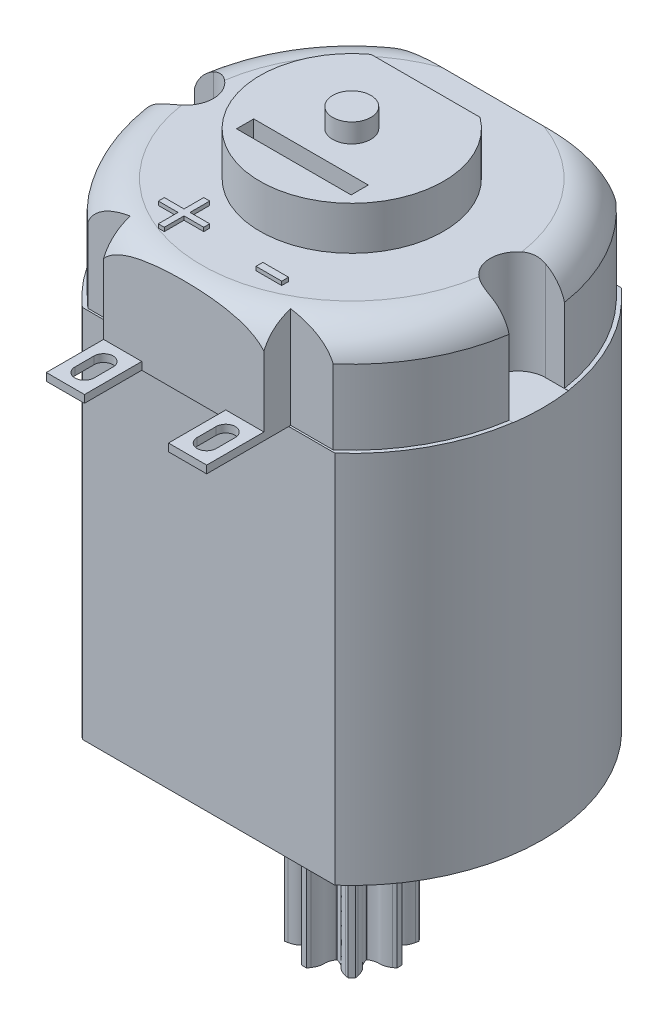
SolidWorks part; units mm, degrees
material "6061-T6 "
ref_plane "Front Plane" through (0, 0, 0) normal (0, 0, 1) x (1, 0, 0)
ref_plane "Top Plane" through (0, 0, 0) normal (0, 1, 0) x (1, 0, 0)
ref_plane "Right Plane" through (0, 0, 0) normal (1, 0, 0) x (0, 0, -1)
sketch "Sketch1" plane through (0, 0, 0) normal (0, 1, 0) x (1, 0, 0)
  line L0 (0, 22.8745) -> (0, 0) construction
  line L1 (0, 0) -> (42.3314, 0) construction
  line L2 (-6.6144, 7.5) -> (6.6144, 7.5)
  line L3 (-6.6144, -7.5) -> (6.6144, -7.5)
  arc A0 (6.6144, -7.5) -> (6.6144, 7.5) centre (0, 0) ccw
  arc A1 (-6.6144, -7.5) -> (-6.6144, 7.5) centre (0, 0) cw
  point P9 (0, 7.5)
  dimension "D1" = 15
  dimension "D2" = 10
extrude "Boss-Extrude1" add sketch "Sketch1" along normal mid plane 19.6
sketch "Sketch2" plane through (0, 9.8, 0) normal (0, 1, 0) x (1, 0, 0)
  line L0 (0, 10.5973) -> (0, 0) construction
  line L1 (0, 0) -> (15.8034, 0) construction
  line L2 (-6.425, 7.4) -> (6.425, 7.4)
  line L3 (-6.425, -7.4) -> (6.425, -7.4)
  arc A0 (6.425, 7.4) -> (6.425, -7.4) centre (0, 0) cw
  arc A1 (-6.425, 7.4) -> (-6.425, -7.4) centre (0, 0) ccw
  point P9 (0, -7.4)
  point P10 (0, 7.4)
  dimension "D1" = 9.8
  dimension "D2" = 14.8
extrude "Boss-Extrude2" add sketch "Sketch2" along normal offset from surface (5.4 mm away) 25 up to face at (0, -9.8, 0)
sketch "Sketch3" plane through (0, 0, 7.4) normal (0, 0, 1) x (1, 0, 0)
  line L0 (-6.425, 9.8) -> (6.425, 9.8) construction
  line L1 (-4.2, 15.2) -> (4.2, 15.2)
  line L2 (-4.2, 15.2) -> (-4.2, 9.8)
  line L3 (-4.2, 9.8) -> (4.2, 9.8)
  line L4 (4.2, 15.2) -> (4.2, 9.8)
  line L5 (-4.2, 15.2) -> (4.2, 9.8) construction
  line L6 (-4.2, 9.8) -> (4.2, 15.2) construction
  line L7 (0, 12.5) -> (0, 0) construction
  line L8 (-6.425, 15.2) -> (6.425, 15.2) construction
  point P0 (0, 12.5)
  dimension "D1" = 8.4
extrude "Boss-Extrude3" add sketch "Sketch3" along normal blind 1.4
sketch "Sketch4" plane through (0, 0, 0) normal (0, 0, 1) x (1, 0, 0)
  line L0 (0, 0) -> (0, 15.2695) construction
  line L1 (7.8635, 15.2) -> (9.8, 15.2)
  line L2 (9.8, 15.2) -> (9.8, 13.7)
  line L3 (9.8, 9.8) -> (9.8, 15.2) construction
  arc A0 (9.8, 13.7) -> (7.8635, 15.2) centre (7.8635, 13.2) ccw
  dimension "D1" = 2
  dimension "D2" = 1.5
revolve "Cut-Revolve1" cut sketch "Sketch4" angle 360 about L0
sketch "Sketch5" plane through (0, 15.2, 0) normal (0, 1, 0) x (1, 0, 0)
  line L0 (-2.8548, 3.865) -> (2.8548, 3.865)
  line L1 (0, -4.805) -> (13.2763, -4.805) construction
  arc A0 (-2.8548, 3.865) -> (2.8548, 3.865) centre (0, 0) ccw
  dimension "D1" = 9.61
  dimension "D3" = 8.67
extrude "Boss-Extrude4" add sketch "Sketch5" along normal blind 2.27
sketch "Sketch6" plane through (0, 17.47, 0) normal (0, 1, 0) x (1, 0, 0)
  line L0 (2.8548, 3.865) -> (-2.8548, 3.865) construction
  line L1 (-3, -2.135) -> (3, -2.135)
  line L2 (-3, -2.135) -> (-3, -3.035)
  line L3 (-3, -3.035) -> (3, -3.035)
  line L4 (3, -2.135) -> (3, -3.035)
  line L5 (-3, -2.135) -> (3, -3.035) construction
  line L6 (-3, -3.035) -> (3, -2.135) construction
  line L7 (0, -2.585) -> (0, 0) construction
  point P0 (0, -2.585)
  dimension "D1" = 6
  dimension "D2" = 0.9
  dimension "D3" = 6
extrude "Cut-Extrude1" cut sketch "Sketch6" against normal up to surface (2.27 mm away) up to face at (0, 15.2, 0.2318)
sketch "Sketch7" plane through (0, -9.8, 0) normal (0, -1, 0) x (1, 0, 0)
  circle A0 centre (0, 0) radius 3
  dimension "D1" = 6
extrude "Boss-Extrude5" add sketch "Sketch7" along normal blind 1.7
sketch "Sketch8" plane through (0, -11.5, 0) normal (0, -1, 0) x (1, 0, 0)
  circle A0 centre (0, 0) radius 1
  dimension "D1" = 2
extrude "Boss-Extrude6" add sketch "Sketch8" along normal offset from surface (7.8 mm away) 9.5 up to face at (0, -9.8, 0) offset beyond the face yes
sketch "Sketch9" plane through (0, -19.3, 0) normal (0, -1, 0) x (1, 0, 0)
  line L0 (0, 0) -> (-1.7678, 1.7678) construction
  line L1 (0, 0) -> (-0.5511, 1.3305) construction
  line L2 (0, 0) -> (-1.3305, 0.5511) construction
  arc A0 (-1.6695, 1.8608) -> (-1.8608, 1.6695) centre (0, 0) ccw
  arc A1 (-0.5874, 1.3368) -> (-0.5511, 1.3305) centre (-0.5363, 1.5249) ccw
  arc A2 (-1.3368, 0.5874) -> (-1.3305, 0.5511) centre (-1.5249, 0.5363) cw
  arc A3 (0.5299, 1.3606) -> (0.5511, 1.3305) centre (0.6991, 1.4575) ccw
  arc A4 (0.1352, 2.4963) -> (-0.1352, 2.4963) centre (0, 0) ccw
  arc A5 (-0.5299, 1.3606) -> (-0.5511, 1.3305) centre (-0.6991, 1.4575) cw
  arc A6 (1.3368, 0.5874) -> (1.3305, 0.5511) centre (1.5249, 0.5363) ccw
  arc A7 (1.8608, 1.6695) -> (1.6695, 1.8608) centre (0, 0) ccw
  arc A8 (0.5874, 1.3368) -> (0.5511, 1.3305) centre (0.5363, 1.5249) cw
  arc A9 (1.3606, -0.5299) -> (1.3305, -0.5511) centre (1.4575, -0.6991) ccw
  arc A10 (2.4963, -0.1352) -> (2.4963, 0.1352) centre (0, 0) ccw
  arc A11 (1.3606, 0.5299) -> (1.3305, 0.5511) centre (1.4575, 0.6991) cw
  arc A12 (0.5874, -1.3368) -> (0.5511, -1.3305) centre (0.5363, -1.5249) ccw
  arc A13 (1.6695, -1.8608) -> (1.8608, -1.6695) centre (0, 0) ccw
  arc A14 (1.3368, -0.5874) -> (1.3305, -0.5511) centre (1.5249, -0.5363) cw
  arc A15 (-0.5299, -1.3606) -> (-0.5511, -1.3305) centre (-0.6991, -1.4575) ccw
  arc A16 (-0.1352, -2.4963) -> (0.1352, -2.4963) centre (0, 0) ccw
  arc A17 (0.5299, -1.3606) -> (0.5511, -1.3305) centre (0.6991, -1.4575) cw
  arc A18 (-1.3368, -0.5874) -> (-1.3305, -0.5511) centre (-1.5249, -0.5363) ccw
  arc A19 (-1.8608, -1.6695) -> (-1.6695, -1.8608) centre (0, 0) ccw
  arc A20 (-0.5874, -1.3368) -> (-0.5511, -1.3305) centre (-0.5363, -1.5249) cw
  arc A21 (-1.3606, 0.5299) -> (-1.3305, 0.5511) centre (-1.4575, 0.6991) ccw
  arc A22 (-2.4963, 0.1352) -> (-2.4963, -0.1352) centre (0, 0) ccw
  arc A23 (-1.3606, -0.5299) -> (-1.3305, -0.5511) centre (-1.4575, -0.6991) cw
  spline S0 degree 3 poles (-0.5874, 1.3368) (-0.6098, 1.3428) (-0.6551, 1.3564) (-0.7224, 1.3803) (-0.7889, 1.4088) (-0.8532, 1.4421) (-0.9142, 1.4808) (-0.9729, 1.5236) (-1.0207, 1.578) (-1.0685, 1.6325) (-1.1272, 1.6753) (-1.1883, 1.714) (-1.2525, 1.7473) (-1.319, 1.7758) (-1.3872, 1.8) (-1.4509, 1.819) (-1.4921, 1.8292) (-1.5099, 1.8333) knots 0.019417 0.019417 0.019417 0.019417 0.074489 0.131742 0.18899 0.246235 0.303478 0.360711 0.417881 0.475052 0.532284 0.589527 0.646773 0.704021 0.761273 0.818526 0.861943 0.861943 0.861943 0.861943 weights 1 1 1 1 1 1 1 1 1 1 1 1 1 1 1 1 1 1
  spline S1 degree 3 poles (-1.5099, 1.8333) (-1.5156, 1.8346) (-1.5448, 1.8411) (-1.5979, 1.8511) (-1.6456, 1.8579) (-1.6695, 1.8608) knots 0.861943 0.861943 0.861943 0.861943 0.87578 0.933034 0.990289 0.990289 0.990289 0.990289 weights 1 1 1 1 1 1
  spline S2 degree 3 poles (-1.3368, 0.5874) (-1.3428, 0.6098) (-1.3564, 0.6551) (-1.3803, 0.7224) (-1.4088, 0.7889) (-1.4421, 0.8532) (-1.4808, 0.9142) (-1.5236, 0.9729) (-1.578, 1.0207) (-1.6325, 1.0685) (-1.6753, 1.1272) (-1.714, 1.1883) (-1.7473, 1.2525) (-1.7758, 1.319) (-1.8, 1.3872) (-1.819, 1.4509) (-1.8292, 1.4921) (-1.8333, 1.5099) knots 0.019417 0.019417 0.019417 0.019417 0.074489 0.131742 0.18899 0.246235 0.303478 0.360711 0.417881 0.475052 0.532284 0.589527 0.646773 0.704021 0.761273 0.818526 0.861943 0.861943 0.861943 0.861943 weights 1 1 1 1 1 1 1 1 1 1 1 1 1 1 1 1 1 1
  spline S3 degree 3 poles (-1.8333, 1.5099) (-1.8346, 1.5156) (-1.8411, 1.5448) (-1.8511, 1.5979) (-1.8579, 1.6456) (-1.8608, 1.6695) knots 0.861943 0.861943 0.861943 0.861943 0.87578 0.933034 0.990289 0.990289 0.990289 0.990289 weights 1 1 1 1 1 1
  spline S4 degree 3 poles (0.5299, 1.3606) (0.5183, 1.3807) (0.4959, 1.4224) (0.4652, 1.4869) (0.4383, 1.554) (0.4164, 1.623) (0.4007, 1.6936) (0.3894, 1.7653) (0.3941, 1.8376) (0.3988, 1.9099) (0.3875, 1.9817) (0.3717, 2.0522) (0.3498, 2.1212) (0.323, 2.1883) (0.2919, 2.2537) (0.2603, 2.3122) (0.2384, 2.3485) (0.2287, 2.364) knots 0.019417 0.019417 0.019417 0.019417 0.074489 0.131742 0.18899 0.246235 0.303478 0.360711 0.417881 0.475052 0.532284 0.589527 0.646773 0.704021 0.761273 0.818526 0.861943 0.861943 0.861943 0.861943 weights 1 1 1 1 1 1 1 1 1 1 1 1 1 1 1 1 1 1
  spline S5 degree 3 poles (0.2287, 2.364) (0.2256, 2.3689) (0.2095, 2.3941) (0.1791, 2.4388) (0.1501, 2.4774) (0.1352, 2.4963) knots 0.861943 0.861943 0.861943 0.861943 0.87578 0.933034 0.990289 0.990289 0.990289 0.990289 weights 1 1 1 1 1 1
  spline S6 degree 3 poles (-0.2287, 2.364) (-0.2256, 2.3689) (-0.2095, 2.3941) (-0.1791, 2.4388) (-0.1501, 2.4774) (-0.1352, 2.4963) knots 0.861943 0.861943 0.861943 0.861943 0.87578 0.933034 0.990289 0.990289 0.990289 0.990289 weights 1 1 1 1 1 1
  spline S7 degree 3 poles (-0.5299, 1.3606) (-0.5183, 1.3807) (-0.4959, 1.4224) (-0.4652, 1.4869) (-0.4383, 1.554) (-0.4164, 1.623) (-0.4007, 1.6936) (-0.3894, 1.7653) (-0.3941, 1.8376) (-0.3988, 1.9099) (-0.3875, 1.9817) (-0.3717, 2.0522) (-0.3498, 2.1212) (-0.323, 2.1883) (-0.2919, 2.2537) (-0.2603, 2.3122) (-0.2384, 2.3485) (-0.2287, 2.364) knots 0.019417 0.019417 0.019417 0.019417 0.074489 0.131742 0.18899 0.246235 0.303478 0.360711 0.417881 0.475052 0.532284 0.589527 0.646773 0.704021 0.761273 0.818526 0.861943 0.861943 0.861943 0.861943 weights 1 1 1 1 1 1 1 1 1 1 1 1 1 1 1 1 1 1
  spline S8 degree 3 poles (1.3368, 0.5874) (1.3428, 0.6098) (1.3564, 0.6551) (1.3803, 0.7224) (1.4088, 0.7889) (1.4421, 0.8532) (1.4808, 0.9142) (1.5236, 0.9729) (1.578, 1.0207) (1.6325, 1.0685) (1.6753, 1.1272) (1.714, 1.1883) (1.7473, 1.2525) (1.7758, 1.319) (1.8, 1.3872) (1.819, 1.4509) (1.8292, 1.4921) (1.8333, 1.5099) knots 0.019417 0.019417 0.019417 0.019417 0.074489 0.131742 0.18899 0.246235 0.303478 0.360711 0.417881 0.475052 0.532284 0.589527 0.646773 0.704021 0.761273 0.818526 0.861943 0.861943 0.861943 0.861943 weights 1 1 1 1 1 1 1 1 1 1 1 1 1 1 1 1 1 1
  spline S9 degree 3 poles (1.8333, 1.5099) (1.8346, 1.5156) (1.8411, 1.5448) (1.8511, 1.5979) (1.8579, 1.6456) (1.8608, 1.6695) knots 0.861943 0.861943 0.861943 0.861943 0.87578 0.933034 0.990289 0.990289 0.990289 0.990289 weights 1 1 1 1 1 1
  spline S10 degree 3 poles (1.5099, 1.8333) (1.5156, 1.8346) (1.5448, 1.8411) (1.5979, 1.8511) (1.6456, 1.8579) (1.6695, 1.8608) knots 0.861943 0.861943 0.861943 0.861943 0.87578 0.933034 0.990289 0.990289 0.990289 0.990289 weights 1 1 1 1 1 1
  spline S11 degree 3 poles (0.5874, 1.3368) (0.6098, 1.3428) (0.6551, 1.3564) (0.7224, 1.3803) (0.7889, 1.4088) (0.8532, 1.4421) (0.9142, 1.4808) (0.9729, 1.5236) (1.0207, 1.578) (1.0685, 1.6325) (1.1272, 1.6753) (1.1883, 1.714) (1.2525, 1.7473) (1.319, 1.7758) (1.3872, 1.8) (1.4509, 1.819) (1.4921, 1.8292) (1.5099, 1.8333) knots 0.019417 0.019417 0.019417 0.019417 0.074489 0.131742 0.18899 0.246235 0.303478 0.360711 0.417881 0.475052 0.532284 0.589527 0.646773 0.704021 0.761273 0.818526 0.861943 0.861943 0.861943 0.861943 weights 1 1 1 1 1 1 1 1 1 1 1 1 1 1 1 1 1 1
  spline S12 degree 3 poles (1.3606, -0.5299) (1.3807, -0.5183) (1.4224, -0.4959) (1.4869, -0.4652) (1.554, -0.4383) (1.623, -0.4164) (1.6936, -0.4007) (1.7653, -0.3894) (1.8376, -0.3941) (1.9099, -0.3988) (1.9817, -0.3875) (2.0522, -0.3717) (2.1212, -0.3498) (2.1883, -0.323) (2.2537, -0.2919) (2.3122, -0.2603) (2.3485, -0.2384) (2.364, -0.2287) knots 0.019417 0.019417 0.019417 0.019417 0.074489 0.131742 0.18899 0.246235 0.303478 0.360711 0.417881 0.475052 0.532284 0.589527 0.646773 0.704021 0.761273 0.818526 0.861943 0.861943 0.861943 0.861943 weights 1 1 1 1 1 1 1 1 1 1 1 1 1 1 1 1 1 1
  spline S13 degree 3 poles (2.364, -0.2287) (2.3689, -0.2256) (2.3941, -0.2095) (2.4388, -0.1791) (2.4774, -0.1501) (2.4963, -0.1352) knots 0.861943 0.861943 0.861943 0.861943 0.87578 0.933034 0.990289 0.990289 0.990289 0.990289 weights 1 1 1 1 1 1
  spline S14 degree 3 poles (2.364, 0.2287) (2.3689, 0.2256) (2.3941, 0.2095) (2.4388, 0.1791) (2.4774, 0.1501) (2.4963, 0.1352) knots 0.861943 0.861943 0.861943 0.861943 0.87578 0.933034 0.990289 0.990289 0.990289 0.990289 weights 1 1 1 1 1 1
  spline S15 degree 3 poles (1.3606, 0.5299) (1.3807, 0.5183) (1.4224, 0.4959) (1.4869, 0.4652) (1.554, 0.4383) (1.623, 0.4164) (1.6936, 0.4007) (1.7653, 0.3894) (1.8376, 0.3941) (1.9099, 0.3988) (1.9817, 0.3875) (2.0522, 0.3717) (2.1212, 0.3498) (2.1883, 0.323) (2.2537, 0.2919) (2.3122, 0.2603) (2.3485, 0.2384) (2.364, 0.2287) knots 0.019417 0.019417 0.019417 0.019417 0.074489 0.131742 0.18899 0.246235 0.303478 0.360711 0.417881 0.475052 0.532284 0.589527 0.646773 0.704021 0.761273 0.818526 0.861943 0.861943 0.861943 0.861943 weights 1 1 1 1 1 1 1 1 1 1 1 1 1 1 1 1 1 1
  spline S16 degree 3 poles (0.5874, -1.3368) (0.6098, -1.3428) (0.6551, -1.3564) (0.7224, -1.3803) (0.7889, -1.4088) (0.8532, -1.4421) (0.9142, -1.4808) (0.9729, -1.5236) (1.0207, -1.578) (1.0685, -1.6325) (1.1272, -1.6753) (1.1883, -1.714) (1.2525, -1.7473) (1.319, -1.7758) (1.3872, -1.8) (1.4509, -1.819) (1.4921, -1.8292) (1.5099, -1.8333) knots 0.019417 0.019417 0.019417 0.019417 0.074489 0.131742 0.18899 0.246235 0.303478 0.360711 0.417881 0.475052 0.532284 0.589527 0.646773 0.704021 0.761273 0.818526 0.861943 0.861943 0.861943 0.861943 weights 1 1 1 1 1 1 1 1 1 1 1 1 1 1 1 1 1 1
  spline S17 degree 3 poles (1.5099, -1.8333) (1.5156, -1.8346) (1.5448, -1.8411) (1.5979, -1.8511) (1.6456, -1.8579) (1.6695, -1.8608) knots 0.861943 0.861943 0.861943 0.861943 0.87578 0.933034 0.990289 0.990289 0.990289 0.990289 weights 1 1 1 1 1 1
  spline S18 degree 3 poles (1.8333, -1.5099) (1.8346, -1.5156) (1.8411, -1.5448) (1.8511, -1.5979) (1.8579, -1.6456) (1.8608, -1.6695) knots 0.861943 0.861943 0.861943 0.861943 0.87578 0.933034 0.990289 0.990289 0.990289 0.990289 weights 1 1 1 1 1 1
  spline S19 degree 3 poles (1.3368, -0.5874) (1.3428, -0.6098) (1.3564, -0.6551) (1.3803, -0.7224) (1.4088, -0.7889) (1.4421, -0.8532) (1.4808, -0.9142) (1.5236, -0.9729) (1.578, -1.0207) (1.6325, -1.0685) (1.6753, -1.1272) (1.714, -1.1883) (1.7473, -1.2525) (1.7758, -1.319) (1.8, -1.3872) (1.819, -1.4509) (1.8292, -1.4921) (1.8333, -1.5099) knots 0.019417 0.019417 0.019417 0.019417 0.074489 0.131742 0.18899 0.246235 0.303478 0.360711 0.417881 0.475052 0.532284 0.589527 0.646773 0.704021 0.761273 0.818526 0.861943 0.861943 0.861943 0.861943 weights 1 1 1 1 1 1 1 1 1 1 1 1 1 1 1 1 1 1
  spline S20 degree 3 poles (-0.5299, -1.3606) (-0.5183, -1.3807) (-0.4959, -1.4224) (-0.4652, -1.4869) (-0.4383, -1.554) (-0.4164, -1.623) (-0.4007, -1.6936) (-0.3894, -1.7653) (-0.3941, -1.8376) (-0.3988, -1.9099) (-0.3875, -1.9817) (-0.3717, -2.0522) (-0.3498, -2.1212) (-0.323, -2.1883) (-0.2919, -2.2537) (-0.2603, -2.3122) (-0.2384, -2.3485) (-0.2287, -2.364) knots 0.019417 0.019417 0.019417 0.019417 0.074489 0.131742 0.18899 0.246235 0.303478 0.360711 0.417881 0.475052 0.532284 0.589527 0.646773 0.704021 0.761273 0.818526 0.861943 0.861943 0.861943 0.861943 weights 1 1 1 1 1 1 1 1 1 1 1 1 1 1 1 1 1 1
  spline S21 degree 3 poles (-0.2287, -2.364) (-0.2256, -2.3689) (-0.2095, -2.3941) (-0.1791, -2.4388) (-0.1501, -2.4774) (-0.1352, -2.4963) knots 0.861943 0.861943 0.861943 0.861943 0.87578 0.933034 0.990289 0.990289 0.990289 0.990289 weights 1 1 1 1 1 1
  spline S22 degree 3 poles (0.2287, -2.364) (0.2256, -2.3689) (0.2095, -2.3941) (0.1791, -2.4388) (0.1501, -2.4774) (0.1352, -2.4963) knots 0.861943 0.861943 0.861943 0.861943 0.87578 0.933034 0.990289 0.990289 0.990289 0.990289 weights 1 1 1 1 1 1
  spline S23 degree 3 poles (0.5299, -1.3606) (0.5183, -1.3807) (0.4959, -1.4224) (0.4652, -1.4869) (0.4383, -1.554) (0.4164, -1.623) (0.4007, -1.6936) (0.3894, -1.7653) (0.3941, -1.8376) (0.3988, -1.9099) (0.3875, -1.9817) (0.3717, -2.0522) (0.3498, -2.1212) (0.323, -2.1883) (0.2919, -2.2537) (0.2603, -2.3122) (0.2384, -2.3485) (0.2287, -2.364) knots 0.019417 0.019417 0.019417 0.019417 0.074489 0.131742 0.18899 0.246235 0.303478 0.360711 0.417881 0.475052 0.532284 0.589527 0.646773 0.704021 0.761273 0.818526 0.861943 0.861943 0.861943 0.861943 weights 1 1 1 1 1 1 1 1 1 1 1 1 1 1 1 1 1 1
  spline S24 degree 3 poles (-1.3368, -0.5874) (-1.3428, -0.6098) (-1.3564, -0.6551) (-1.3803, -0.7224) (-1.4088, -0.7889) (-1.4421, -0.8532) (-1.4808, -0.9142) (-1.5236, -0.9729) (-1.578, -1.0207) (-1.6325, -1.0685) (-1.6753, -1.1272) (-1.714, -1.1883) (-1.7473, -1.2525) (-1.7758, -1.319) (-1.8, -1.3872) (-1.819, -1.4509) (-1.8292, -1.4921) (-1.8333, -1.5099) knots 0.019417 0.019417 0.019417 0.019417 0.074489 0.131742 0.18899 0.246235 0.303478 0.360711 0.417881 0.475052 0.532284 0.589527 0.646773 0.704021 0.761273 0.818526 0.861943 0.861943 0.861943 0.861943 weights 1 1 1 1 1 1 1 1 1 1 1 1 1 1 1 1 1 1
  spline S25 degree 3 poles (-1.8333, -1.5099) (-1.8346, -1.5156) (-1.8411, -1.5448) (-1.8511, -1.5979) (-1.8579, -1.6456) (-1.8608, -1.6695) knots 0.861943 0.861943 0.861943 0.861943 0.87578 0.933034 0.990289 0.990289 0.990289 0.990289 weights 1 1 1 1 1 1
  spline S26 degree 3 poles (-1.5099, -1.8333) (-1.5156, -1.8346) (-1.5448, -1.8411) (-1.5979, -1.8511) (-1.6456, -1.8579) (-1.6695, -1.8608) knots 0.861943 0.861943 0.861943 0.861943 0.87578 0.933034 0.990289 0.990289 0.990289 0.990289 weights 1 1 1 1 1 1
  spline S27 degree 3 poles (-0.5874, -1.3368) (-0.6098, -1.3428) (-0.6551, -1.3564) (-0.7224, -1.3803) (-0.7889, -1.4088) (-0.8532, -1.4421) (-0.9142, -1.4808) (-0.9729, -1.5236) (-1.0207, -1.578) (-1.0685, -1.6325) (-1.1272, -1.6753) (-1.1883, -1.714) (-1.2525, -1.7473) (-1.319, -1.7758) (-1.3872, -1.8) (-1.4509, -1.819) (-1.4921, -1.8292) (-1.5099, -1.8333) knots 0.019417 0.019417 0.019417 0.019417 0.074489 0.131742 0.18899 0.246235 0.303478 0.360711 0.417881 0.475052 0.532284 0.589527 0.646773 0.704021 0.761273 0.818526 0.861943 0.861943 0.861943 0.861943 weights 1 1 1 1 1 1 1 1 1 1 1 1 1 1 1 1 1 1
  spline S28 degree 3 poles (-1.3606, 0.5299) (-1.3807, 0.5183) (-1.4224, 0.4959) (-1.4869, 0.4652) (-1.554, 0.4383) (-1.623, 0.4164) (-1.6936, 0.4007) (-1.7653, 0.3894) (-1.8376, 0.3941) (-1.9099, 0.3988) (-1.9817, 0.3875) (-2.0522, 0.3717) (-2.1212, 0.3498) (-2.1883, 0.323) (-2.2537, 0.2919) (-2.3122, 0.2603) (-2.3485, 0.2384) (-2.364, 0.2287) knots 0.019417 0.019417 0.019417 0.019417 0.074489 0.131742 0.18899 0.246235 0.303478 0.360711 0.417881 0.475052 0.532284 0.589527 0.646773 0.704021 0.761273 0.818526 0.861943 0.861943 0.861943 0.861943 weights 1 1 1 1 1 1 1 1 1 1 1 1 1 1 1 1 1 1
  spline S29 degree 3 poles (-2.364, 0.2287) (-2.3689, 0.2256) (-2.3941, 0.2095) (-2.4388, 0.1791) (-2.4774, 0.1501) (-2.4963, 0.1352) knots 0.861943 0.861943 0.861943 0.861943 0.87578 0.933034 0.990289 0.990289 0.990289 0.990289 weights 1 1 1 1 1 1
  spline S30 degree 3 poles (-2.364, -0.2287) (-2.3689, -0.2256) (-2.3941, -0.2095) (-2.4388, -0.1791) (-2.4774, -0.1501) (-2.4963, -0.1352) knots 0.861943 0.861943 0.861943 0.861943 0.87578 0.933034 0.990289 0.990289 0.990289 0.990289 weights 1 1 1 1 1 1
  spline S31 degree 3 poles (-1.3606, -0.5299) (-1.3807, -0.5183) (-1.4224, -0.4959) (-1.4869, -0.4652) (-1.554, -0.4383) (-1.623, -0.4164) (-1.6936, -0.4007) (-1.7653, -0.3894) (-1.8376, -0.3941) (-1.9099, -0.3988) (-1.9817, -0.3875) (-2.0522, -0.3717) (-2.1212, -0.3498) (-2.1883, -0.323) (-2.2537, -0.2919) (-2.3122, -0.2603) (-2.3485, -0.2384) (-2.364, -0.2287) knots 0.019417 0.019417 0.019417 0.019417 0.074489 0.131742 0.18899 0.246235 0.303478 0.360711 0.417881 0.475052 0.532284 0.589527 0.646773 0.704021 0.761273 0.818526 0.861943 0.861943 0.861943 0.861943 weights 1 1 1 1 1 1 1 1 1 1 1 1 1 1 1 1 1 1
  point P85 (0, 0)
extrude "Boss-Extrude7" add sketch "Sketch9" against normal blind 5
sketch "Sketch10" plane through (0, 15.2, 0) normal (0, 1, 0) x (1, 0, 0)
  line L0 (-11.4198, 0) -> (-8.7, 0) construction
  line L1 (-11.4198, 1.45) -> (-8.7, 1.45)
  line L2 (-11.4198, -1.45) -> (-8.7, -1.45)
  line L3 (0, 0) -> (0, -11.9307) construction
  line L4 (-7.25, 0) -> (-7.25, -11.1918) construction
  line L5 (11.4198, 0) -> (8.7, 0) construction
  line L6 (11.4198, 1.45) -> (8.7, 1.45)
  line L7 (11.4198, -1.45) -> (8.7, -1.45)
  arc A0 (-11.4198, 1.45) -> (-11.4198, -1.45) centre (-11.4198, 0) ccw
  arc A1 (-8.7, -1.45) -> (-8.7, 1.45) centre (-8.7, 0) ccw
  arc A2 (11.4198, 1.45) -> (11.4198, -1.45) centre (11.4198, 0) cw
  arc A3 (8.7, -1.45) -> (8.7, 1.45) centre (8.7, 0) cw
  point P4 (-10.0599, 0)
  point P16 (10.0599, 0)
  dimension "D1" = 2.9
  dimension "D2" = 14.5
  dimension "D3" = 2.7198
extrude "Cut-Extrude2" cut sketch "Sketch10" against normal blind 5.41
sketch "Sketch11" plane through (0, 17.47, 0) normal (0, 1, 0) x (1, 0, 0)
  circle A0 centre (0, 0) radius 1
  dimension "D1" = 2
extrude "Boss-Extrude8" add sketch "Sketch11" along normal blind 1
sketch "Sketch12" plane through (0, 0, 8.8) normal (0, 0, 1) x (1, 0, 0)
  line L0 (-4.2, 9.8) -> (4.2, 9.8) construction
  line L1 (-2.2, 10.2) -> (-4.2, 10.2)
  line L2 (-2.2, 10.2) -> (-2.2, 9.8)
  line L3 (-2.2, 9.8) -> (-4.2, 9.8)
  line L4 (-4.2, 10.2) -> (-4.2, 9.8)
  line L5 (-2.2, 10.2) -> (-4.2, 9.8) construction
  line L6 (-2.2, 9.8) -> (-4.2, 10.2) construction
  line L7 (0, 0) -> (0, 7.8407) construction
  line L8 (2.2, 9.8) -> (4.2, 10.2) construction
  line L9 (2.2, 10.2) -> (4.2, 9.8) construction
  line L10 (4.2, 10.2) -> (4.2, 9.8)
  line L11 (2.2, 9.8) -> (4.2, 9.8)
  line L12 (2.2, 10.2) -> (2.2, 9.8)
  line L13 (2.2, 10.2) -> (4.2, 10.2)
  point P0 (-3.2, 10)
  point P15 (3.2, 10)
  dimension "D1" = 2
  dimension "D2" = 0.4
extrude "Boss-Extrude9" add sketch "Sketch12" along normal blind 3
sketch "Sketch13" plane through (0, 10.2, 0) normal (0, 1, 0) x (1, 0, 0)
  line L0 (-3.2, -9.8) -> (-3.2, -10.8) construction
  line L1 (-2.7, -9.8) -> (-2.7, -10.8)
  line L2 (-3.7, -9.8) -> (-3.7, -10.8)
  line L3 (-4.2, -11.8) -> (-4.2, -8.8) construction
  line L4 (-4.2, -10.3) -> (-2.2, -10.3) construction
  line L5 (-2.2, -11.8) -> (-2.2, -8.8) construction
  line L6 (0, 0) -> (0, -18.1242) construction
  line L7 (4.2, -10.3) -> (2.2, -10.3) construction
  line L8 (3.2, -9.8) -> (3.2, -10.8) construction
  line L9 (2.7, -9.8) -> (2.7, -10.8)
  line L10 (3.7, -9.8) -> (3.7, -10.8)
  arc A0 (-2.7, -9.8) -> (-3.7, -9.8) centre (-3.2, -9.8) ccw
  arc A1 (-3.7, -10.8) -> (-2.7, -10.8) centre (-3.2, -10.8) ccw
  arc A2 (2.7, -9.8) -> (3.7, -9.8) centre (3.2, -9.8) cw
  arc A3 (3.7, -10.8) -> (2.7, -10.8) centre (3.2, -10.8) cw
  point P2 (-3.2, -10.3)
  point P20 (3.2, -10.3)
  dimension "D1" = 1
  dimension "D2" = 1
  dimension "D3" = 1
extrude "Cut-Extrude3" cut sketch "Sketch13" against normal through all
sketch "Sketch14" plane through (0, 15.2, 0) normal (0, 1, 0) x (1, 0, 0)
  text T0 "+  -"
extrude "Boss-Extrude10" add sketch "Sketch14" along normal blind 0.2
